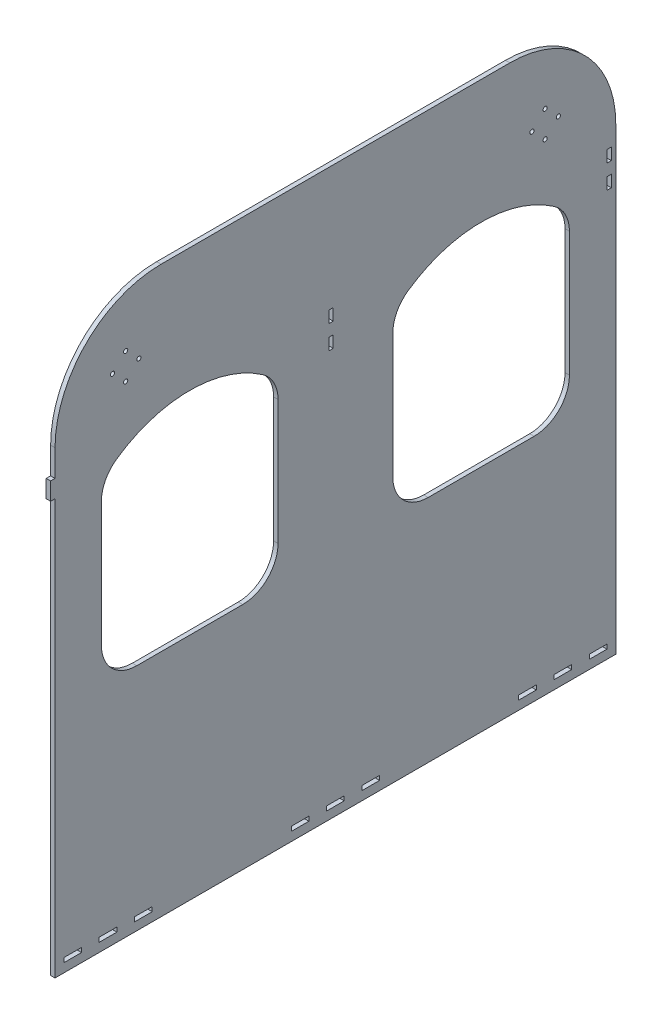
SolidWorks part; units mm, degrees
ref_plane "Front Plane" through (0, 0, 0) normal (0, 0, 1) x (1, 0, 0)
ref_plane "Top Plane" through (0, 0, 0) normal (0, 1, 0) x (1, 0, 0)
ref_plane "Right Plane" through (0, 0, 0) normal (1, 0, 0) x (0, 0, -1)
sketch "Sketch1" plane through (0, 0, 0) normal (1, 0, 0) x (0, 0, -1)
  line L1 (-201.6125, -203.2) -> (201.6125, -203.2)
  line L2 (-201.6125, -203.2) -> (-201.6125, 127)
  line L3 (-125.4125, 203.2) -> (125.4125, 203.2)
  line L4 (201.6125, -203.2) -> (201.6125, 127)
  line L5 (-201.6125, -203.2) -> (201.6125, 203.2) construction
  line L6 (-201.6125, 203.2) -> (201.6125, -203.2) construction
  arc A0 (125.4125, 203.2) -> (201.6125, 127) centre (125.4125, 127) cw
  arc A1 (-201.6125, 127) -> (-125.4125, 203.2) centre (-125.4125, 127) cw
  point P0 (0, 0)
  point P6 (0, 0)
  dimension "D3" = 76.2
  dimension "D1" = 406.4
  dimension "D2" = 403.225
extrude "Boss-Extrude1" add sketch "Sketch1" along normal blind 3.175
sketch "Sketch2" plane through (3.175, 0, 0) normal (1, 0, 0) x (0, 0, -1)
  line L0 (-201.6125, 101.6) -> (201.6125, 101.6) construction
  line L1 (-201.6125, 127) -> (-201.6125, -203.2) construction
  line L2 (201.6125, -203.2) -> (201.6125, 127) construction
  line L3 (125.4125, 203.2) -> (-125.4125, 203.2) construction
  line L4 (-1.5875, 114.3) -> (-4.7625, 114.3)
  line L5 (195.2625, 114.3) -> (198.4375, 114.3)
  line L6 (195.2625, 114.3) -> (195.2625, 105.8333)
  line L7 (195.2625, 105.8333) -> (198.4375, 105.8333)
  line L8 (198.4375, 114.3) -> (198.4375, 105.8333)
  line L9 (195.2625, 114.3) -> (198.4375, 105.8333) construction
  line L10 (195.2625, 105.8333) -> (198.4375, 114.3) construction
  line L11 (195.2625, 97.3667) -> (198.4375, 97.3667)
  line L12 (195.2625, 97.3667) -> (195.2625, 88.9)
  line L13 (195.2625, 88.9) -> (198.4375, 88.9)
  line L14 (198.4375, 97.3667) -> (198.4375, 88.9)
  line L15 (195.2625, 97.3667) -> (198.4375, 88.9) construction
  line L16 (195.2625, 88.9) -> (198.4375, 97.3667) construction
  line L17 (-1.5875, 114.3) -> (-1.5875, 105.8333)
  line L18 (-1.5875, 105.8333) -> (-4.7625, 105.8333)
  line L19 (-4.7625, 114.3) -> (-4.7625, 105.8333)
  line L20 (-1.5875, 97.3667) -> (-4.7625, 97.3667)
  line L21 (-1.5875, 97.3667) -> (-1.5875, 88.9)
  line L22 (-1.5875, 88.9) -> (-4.7625, 88.9)
  line L23 (-4.7625, 97.3667) -> (-4.7625, 88.9)
  point P8 (196.85, 110.0667)
  point P13 (196.85, 93.1333)
  point P18 (0, 0)
  point P27 (0, 0)
  dimension "D1" = 101.6
  dimension "D2" = 3.175
  dimension "D3" = 8.4667
  dimension "D4" = 4.2333
  dimension "D5" = 4.2333
  dimension "D6" = 3.175
  dimension "D7" = 3.175
  dimension "D8" = 8.4667
  dimension "D9" = 4.2333
  dimension "D10" = 4.2333
  dimension "D11" = 200.025
extrude "Cut-Extrude1" cut sketch "Sketch2" against normal blind 3.175
sketch "Sketch3" plane through (0, 0, 201.6125) normal (0, 0, 1) x (1, 0, 0)
  line L0 (0, 127) -> (0, -203.2) construction
  line L1 (0, 107.95) -> (3.175, 107.95)
  line L2 (0, 107.95) -> (0, 95.25)
  line L3 (0, 95.25) -> (3.175, 95.25)
  line L4 (3.175, 107.95) -> (3.175, 95.25)
  line L5 (3.175, 127) -> (3.175, -203.2) construction
  line L6 (0, 101.6) -> (3.175, 101.6) construction
  line L11 (3.175, 203.2) -> (0, 203.2) construction
  point P8 (0, 101.6)
  dimension "D1" = 101.6
  dimension "D2" = 12.7
extrude "Boss-Extrude2" add sketch "Sketch3" along normal blind 3.175
sketch "Sketch4" plane through (3.175, 0, 0) normal (1, 0, 0) x (0, 0, -1)
  line L0 (-201.6125, 88.9) -> (201.6125, 88.9) construction
  line L1 (-201.6125, 95.25) -> (-201.6125, -203.2) construction
  line L2 (201.6125, -203.2) -> (201.6125, 127) construction
  line L3 (-204.7875, 95.25) -> (-201.6125, 95.25) construction
  line L4 (-1.5875, 97.3667) -> (-4.7625, 97.3667) construction
  line L6 (-168.275, 76.942) -> (-168.275, -12.7)
  line L7 (-142.875, -38.1) -> (-66.675, -38.1)
  line L8 (-41.275, 76.942) -> (-41.275, -12.7)
  line L13 (0, 55) -> (0, -55) construction
  line L14 (168.275, 76.942) -> (168.275, -12.7)
  line L15 (142.875, -38.1) -> (66.675, -38.1)
  line L16 (41.275, 76.942) -> (41.275, -12.7)
  arc A2 (-66.675, -38.1) -> (-41.275, -12.7) centre (-66.675, -12.7) ccw
  arc A3 (-168.275, -12.7) -> (-142.875, -38.1) centre (-142.875, -12.7) ccw
  arc A5 (-157.3893, 97.7865) -> (-52.1607, 97.7865) centre (-104.775, 22.225) cw
  arc A6 (-52.1607, 97.7865) -> (-41.275, 76.942) centre (-66.675, 76.942) cw
  arc A7 (-157.3893, 97.7865) -> (-168.275, 76.942) centre (-142.875, 76.942) ccw
  arc A8 (157.3893, 97.7865) -> (168.275, 76.942) centre (142.875, 76.942) cw
  arc A9 (168.275, -12.7) -> (142.875, -38.1) centre (142.875, -12.7) cw
  arc A10 (66.675, -38.1) -> (41.275, -12.7) centre (66.675, -12.7) cw
  arc A11 (52.1607, 97.7865) -> (41.275, 76.942) centre (66.675, 76.942) ccw
  arc A12 (157.3893, 97.7865) -> (52.1607, 97.7865) centre (104.775, 22.225) ccw
  point P18 (-3.175, 97.3667)
  point P27 (-168.275, -38.1)
  point P29 (-104.775, 114.3)
  point P30 (0, 0)
  point P33 (-41.275, 88.9)
  point P36 (-168.275, 88.9)
  dimension "D8" = 25.4
  dimension "D2" = 25.4
  dimension "D1" = 6.35
  dimension "D3" = 127
  dimension "D4" = 38.1
  dimension "D5" = 25.4
  dimension "D6" = 127
  dimension "D9" = 127
extrude "Cut-Extrude2" cut sketch "Sketch4" against normal blind 3.175
sketch "Sketch5" plane through (3.175, 0, 0) normal (1, 0, 0) x (0, 0, -1)
  line L0 (-201.6125, 95.25) -> (-201.6125, -203.2) construction
  line L1 (-195.2625, -196.85) -> (-182.5625, -196.85)
  line L2 (-195.2625, -196.85) -> (-195.2625, -193.675)
  line L3 (-195.2625, -193.675) -> (-182.5625, -193.675)
  line L4 (-182.5625, -196.85) -> (-182.5625, -193.675)
  line L5 (-195.2625, -196.85) -> (-182.5625, -193.675) construction
  line L6 (-195.2625, -193.675) -> (-182.5625, -196.85) construction
  line L7 (-201.6125, -203.2) -> (201.6125, -203.2) construction
  line L8 (-169.8625, -196.85) -> (-169.8625, -193.675)
  line L9 (-169.8625, -196.85) -> (-157.1625, -196.85)
  line L10 (-157.1625, -196.85) -> (-157.1625, -193.675)
  line L11 (-169.8625, -193.675) -> (-157.1625, -193.675)
  line L12 (-144.4625, -196.85) -> (-144.4625, -193.675)
  line L13 (-144.4625, -196.85) -> (-131.7625, -196.85)
  line L14 (-131.7625, -196.85) -> (-131.7625, -193.675)
  line L15 (-144.4625, -193.675) -> (-131.7625, -193.675)
  point P0 (-188.9125, -195.2625)
  dimension "D1" = 12.7
  dimension "D2" = 6.35
  dimension "D3" = 6.35
  dimension "D4" = 3.175
  dimension "D6" = 12.7
  dimension "D5" = 3
extrude "Cut-Extrude3" cut sketch "Sketch5" against normal blind 3.175
mirror "Mirror1" about plane through (0, 0, 0) normal (0, 0, 1) of "Cut-Extrude3"
sketch "Sketch6" plane through (3.175, 0, 0) normal (1, 0, 0) x (0, 0, -1)
  line L0 (-144.4625, -196.85) -> (-131.7625, -196.85) construction
  line L1 (-31.75, -196.85) -> (-19.05, -196.85)
  line L2 (-31.75, -196.85) -> (-31.75, -193.675)
  line L3 (-31.75, -193.675) -> (-19.05, -193.675)
  line L4 (-19.05, -196.85) -> (-19.05, -193.675)
  line L5 (-31.75, -196.85) -> (-19.05, -193.675) construction
  line L6 (-31.75, -193.675) -> (-19.05, -196.85) construction
  line L7 (-6.35, -196.85) -> (-6.35, -193.675)
  line L8 (-6.35, -196.85) -> (6.35, -196.85)
  line L9 (6.35, -196.85) -> (6.35, -193.675)
  line L10 (-6.35, -193.675) -> (6.35, -193.675)
  line L11 (19.05, -196.85) -> (19.05, -193.675)
  line L12 (19.05, -196.85) -> (31.75, -196.85)
  line L13 (31.75, -196.85) -> (31.75, -193.675)
  line L14 (19.05, -193.675) -> (31.75, -193.675)
  point P0 (-25.4, -195.2625)
  dimension "D1" = 100.0125
  dimension "D2" = 12.7
  dimension "D3" = 3.175
  dimension "D5" = 12.7
  dimension "D4" = 3
extrude "Cut-Extrude4" cut sketch "Sketch6" against normal blind 3.175
sketch "Sketch7" plane through (3.175, 0, 0) normal (1, 0, 0) x (0, 0, -1)
  line L0 (-150.8125, 161.9) -> (-160.3125, 152.4)
  line L1 (-160.3125, 152.4) -> (-150.8125, 142.9)
  line L2 (-150.8125, 142.9) -> (-141.3125, 152.4)
  line L3 (-141.3125, 152.4) -> (-150.8125, 161.9)
  line L4 (-201.6125, 127) -> (-201.6125, 107.95) construction
  line L5 (125.4125, 203.2) -> (-125.4125, 203.2) construction
  circle A0 centre (-150.8125, 161.9) radius 1.5
  circle A1 centre (-141.3125, 152.4) radius 1.5
  circle A2 centre (-150.8125, 142.9) radius 1.5
  circle A3 centre (-160.3125, 152.4) radius 1.5
  point P8 (0, 0)
  dimension "D2" = 3
  dimension "D1" = 19
  dimension "D3" = 50.8
  dimension "D4" = 50.8
extrude "Cut-Extrude5" cut sketch "Sketch7" against normal blind 3.175 contours L0 A3 L1 | L3 A0 L0 | L2 A1 L3 | L1 A2 L2 | L1 A3 L0 | L0 A0 L3 | L3 A1 L2 | L2 A2 L1
mirror "Mirror2" about plane through (0, 0, 0) normal (0, 0, 1) of "Cut-Extrude5"
